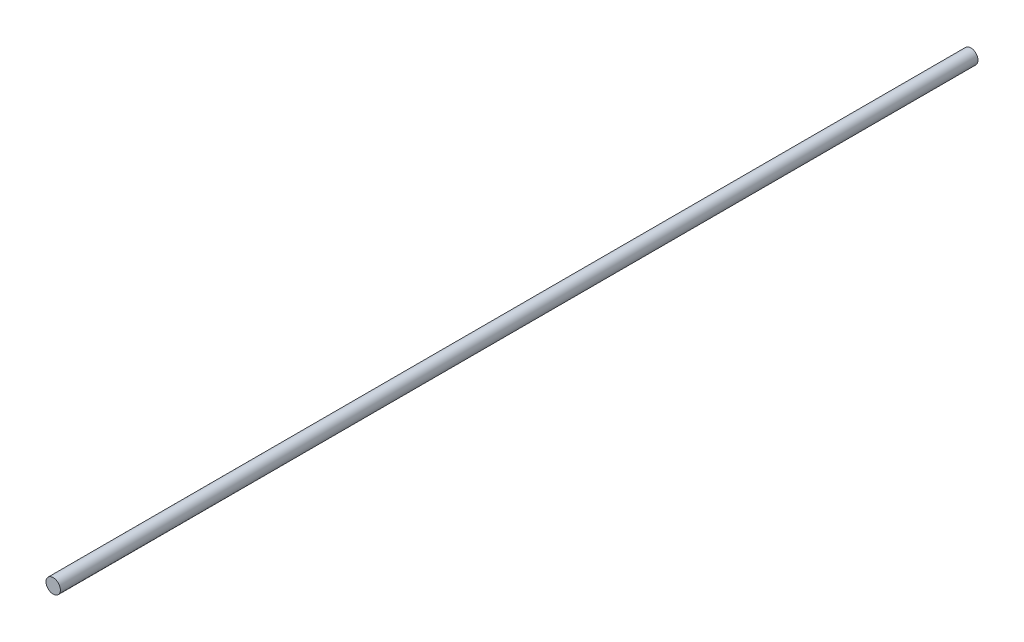
SolidWorks part; units mm, degrees
ref_plane "Plan de face" through (0, 0, 0) normal (0, 0, 1) x (1, 0, 0)
ref_plane "Plan de dessus" through (0, 0, 0) normal (0, 1, 0) x (1, 0, 0)
ref_plane "Plan de droite" through (0, 0, 0) normal (1, 0, 0) x (0, 0, -1)
sketch "Esquisse1" plane through (0, 0, 0) normal (0, 0, 1) x (1, 0, 0)
  circle A0 centre (0, 0) radius 5
  dimension "D1" = 10
extrude "Boss.-Extru.1" add sketch "Esquisse1" along normal blind 638
